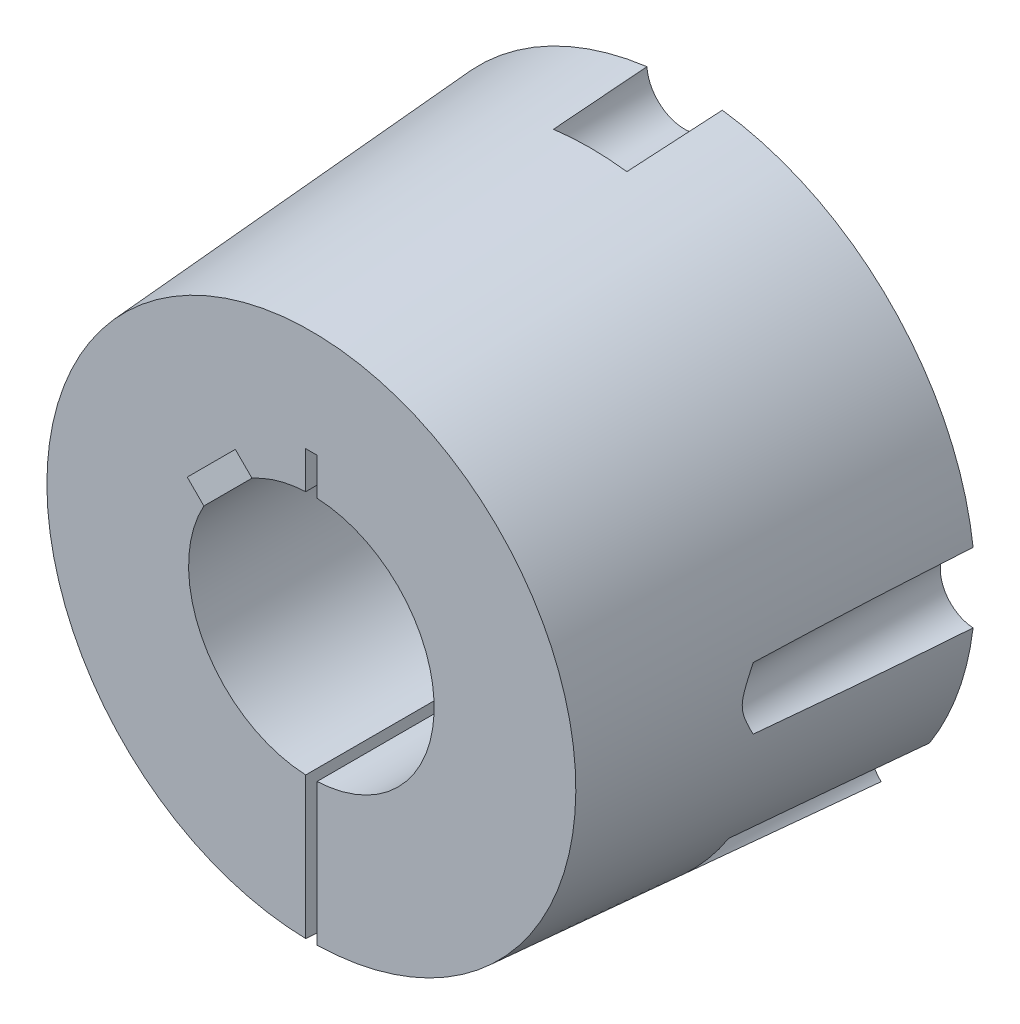
SolidWorks part; units mm, degrees
ref_plane "Front Plane" through (0, 0, 0) normal (0, 0, 1) x (1, 0, 0)
ref_plane "Top Plane" through (0, 0, 0) normal (0, 1, 0) x (1, 0, 0)
ref_plane "Right Plane" through (0, 0, 0) normal (1, 0, 0) x (0, 0, -1)
sketch "Sketch1" plane through (0, 0, 0) normal (1, 0, 0) x (0, 0, -1)
  line L0 (528.4547, 1007.3052) -> (528.4547, 969.8052)
  line L1 (627.2547, 1014.214) -> (627.2547, 969.8052)
  line L2 (528.4547, 1007.3052) -> (627.2547, 1014.214)
  line L3 (528.4547, 937.3052) -> (627.2547, 937.3052)
  line L5 (532.5672, 969.8052) -> (611.2383, 969.8052)
  line L6 (611.2383, 969.8052) -> (627.2547, 969.8052)
  line L7 (532.5672, 969.8052) -> (528.4547, 969.8052)
  dimension "D2" = 32.5
revolve "Revolve1" add sketch "Sketch1" angle 360 about L3
sketch "Sketch2" plane through (0, 0, -627.2547) normal (0, 0, -1) x (-1, 0, 0)
  circle A0 centre (76.9088, 937.3052) radius 6.3657
  circle A1 centre (0, 937.3052) radius 76.9088 construction
hole_wizard "M20x1.5 Tapped Hole1" positions "Sketch5" profile "Sketch6" tap size "M20x1.5" standard "DIN"
sketch "Sketch5" plane through (0, 0, -627.2547) normal (0, 0, -1) x (-1, 0, 0)
  point P0 (76.9088, 937.3052)
sketch "Sketch6" plane through (-76.9088, 937.3052, -627.2547) normal (1, 0, 0) x (0, 1, 0)
  line L0 (0, 0) -> (0, 60.058)
  line L1 (0, 60.058) -> (9.25, 54.5)
  line L2 (9.25, 54.5) -> (9.25, 0)
  line L5 (9.25, 0) -> (0, 0)
  line L10 (0, 60.058) -> (-9.25, 54.5) construction
  line L11 (0, -6.35) -> (0, 107.95) construction
  dimension "Tap Drill Dia." = 18.5
  dimension "Tap Drill Depth" = 54.5
  dimension "Drill Angle" = 118
cosmetic thread "Hole Thread1" parameters "D1"=50, "D2"=20
pattern_circular "CirPattern1" count 2 every 180 about axis through (0, 937.3052, 0) along (0, 0, 1) of "M20x1.5 Tapped Hole1"
sketch "Sketch7" plane through (0, 0, -627.2547) normal (0, 0, -1) x (-1, 0, 0)
  circle A0 centre (0, 1014.214) radius 10
  arc A1 (76.3525, 946.5384) -> (-76.3525, 946.5384) centre (0, 937.3052) ccw construction
  dimension "D1" = 20
extrude "Cut-Extrude1" cut sketch "Sketch7" against normal blind 25
pattern_circular "CirPattern2" count 2 every 130 about axis through (0, 937.3052, -627.2547) along (0, 0, 1) of "Cut-Extrude1"
sketch "Sketch8" plane through (0, 0, -627.2547) normal (0, 0, -1) x (-1, 0, 0)
  circle A0 centre (0, 860.3964) radius 10
  arc A1 (-52.0032, 880.6428) -> (76.3525, 928.0719) centre (0, 937.3052) ccw construction
  dimension "D1" = 20
extrude "Cut-Extrude2" cut sketch "Sketch8" against normal blind 50
pattern_circular "CirPattern3" count 2 every 50 about axis through (0, 937.3052, -627.2547) along (0, 0, 1) of "Cut-Extrude2"
sketch "Sketch9" plane through (0, 0, -627.2547) normal (0, 0, -1) x (-1, 0, 0)
  line L0 (1.5, 937.3052) -> (-1.5, 937.3052)
  line L1 (-1.5, 937.3052) -> (-1.5, 850.089)
  line L2 (1.5, 937.3052) -> (1.5, 850.089)
  line L3 (1.5, 850.089) -> (-1.5, 850.089)
extrude "Cut-Extrude3" cut sketch "Sketch9" against normal through all both and the other way through all
sketch "Sketch10" plane through (0, 0, -627.2547) normal (0, 0, -1) x (-1, 0, 0)
  line L1 (1.5, 957.3052) -> (1.5, 979.6393)
  line L2 (-1.5, 957.3052) -> (-1.5, 979.6393)
  line L3 (1.5, 957.3052) -> (1.5, 953.7305)
  line L4 (1.5, 953.7305) -> (-1.5, 953.7305)
  line L5 (-1.5, 953.7305) -> (-1.5, 957.3052)
  line L6 (-1.5, 979.6393) -> (1.5, 979.6393)
  point P0 (1.5, 979.6393)
extrude "Cut-Extrude4" cut sketch "Sketch10" against normal through all both and the other way through all
sketch "Sketch12" plane through (0, 0, -627.2547) normal (0, 0, -1) x (-1, 0, 0)
  circle A0 centre (-58.9155, 887.8692) radius 10
extrude "Cut-Extrude6" cut sketch "Sketch12" against normal blind 50
sketch "Sketch13" plane through (0, 0, -627.2547) normal (0, 0, -1) x (-1, 0, 0)
  line L2 (13.057, 963.0901) -> (25.7849, 950.3622)
  line L3 (13.057, 963.0901) -> (20.1281, 970.1612)
  line L4 (20.1281, 970.1612) -> (32.856, 957.4332)
  line L5 (25.7849, 950.3622) -> (32.856, 957.4332)
  line L6 (13.057, 963.0901) -> (32.856, 957.4332) construction
  line L7 (20.1281, 970.1612) -> (25.7849, 950.3622) construction
  point P4 (22.9565, 960.2617)
  dimension "D1" = 18
  dimension "D2" = 10
extrude "Cut-Extrude7" cut sketch "Sketch13" against normal through all both and the other way through all
